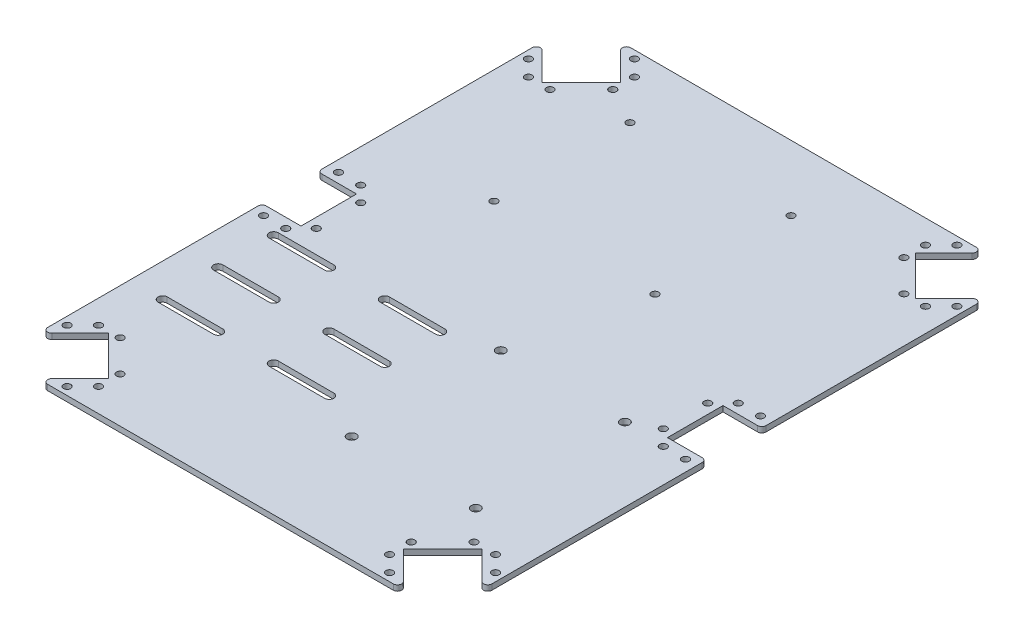
SolidWorks part; units mm, degrees
ref_plane "Front Plane" through (0, 0, 0) normal (0, 0, 1) x (1, 0, 0)
ref_plane "Top Plane" through (0, 0, 0) normal (0, 1, 0) x (1, 0, 0)
ref_plane "Right Plane" through (0, 0, 0) normal (1, 0, 0) x (0, 0, -1)
sketch "Sketch2" plane through (0, 0, 0) normal (0, 1, 0) x (1, 0, 0)
  line L0 (-80, 0) -> (80, 0) construction
  line L1 (-80, 105) -> (80, 105)
  line L2 (-80, 105) -> (-80, -105)
  line L3 (-80, -105) -> (80, -105)
  line L4 (80, 105) -> (80, -105)
  line L5 (80, 105) -> (0, 25) construction
  line L7 (0, 105) -> (0, -105) construction
  line L8 (52.4228, 88.7365) -> (48.5337, 92.6256) construction
  line L9 (48.5337, 92.6256) -> (52.4228, 96.5147) construction
  line L10 (52.4228, 96.5147) -> (58.0797, 102.1716) construction
  line L11 (58.0797, 102.1716) -> (60.9081, 105) construction
  circle A5 centre (52.4228, 88.7365) radius 1.3
  circle A6 centre (52.4228, 96.5147) radius 1.3
  circle A7 centre (58.0797, 102.1716) radius 1.3
  circle A8 centre (76, 13.5) radius 1.3
  circle A9 centre (68, 13.5) radius 1.3
  circle A10 centre (62.5, 8) radius 1.3
  circle A11 centre (62.5, -8) radius 1.3
  circle A12 centre (68, -13.5) radius 1.3
  circle A13 centre (76, -13.5) radius 1.3
  circle A14 centre (77.1716, 83.0797) radius 1.3
  circle A15 centre (71.5147, 77.4228) radius 1.3
  circle A16 centre (63.7365, 77.4228) radius 1.3
  circle A17 centre (77.1716, -83.0797) radius 1.3
  circle A18 centre (71.5147, -77.4228) radius 1.3
  circle A19 centre (63.7365, -77.4228) radius 1.3
  circle A20 centre (58.0797, -102.1716) radius 1.3
  circle A21 centre (52.4228, -96.5147) radius 1.3
  circle A22 centre (52.4228, -88.7365) radius 1.3
  circle A23 centre (-58.0797, 102.1716) radius 1.3
  circle A24 centre (-52.4228, 96.5147) radius 1.3
  circle A25 centre (-52.4228, 88.7365) radius 1.3
  circle A26 centre (-77.1716, 83.0797) radius 1.3
  circle A27 centre (-71.5147, 77.4228) radius 1.3
  circle A28 centre (-63.7365, 77.4228) radius 1.3
  circle A29 centre (-77.1716, -83.0797) radius 1.3
  circle A30 centre (-71.5147, -77.4228) radius 1.3
  circle A31 centre (-63.7365, -77.4228) radius 1.3
  circle A32 centre (-52.4228, -88.7365) radius 1.3
  circle A33 centre (-52.4228, -96.5147) radius 1.3
  circle A34 centre (-58.0797, -102.1716) radius 1.3
  circle A35 centre (-62.5, -8) radius 1.3
  circle A36 centre (-68, -13.5) radius 1.3
  circle A37 centre (-76, -13.5) radius 1.3
  circle A38 centre (-76, 13.5) radius 1.3
  circle A39 centre (-68, 13.5) radius 1.3
  circle A40 centre (-62.5, 8) radius 1.3
  point P0 (0, 0)
  point P27 (0, 0)
  dimension "D6" = 5.5
  dimension "D10" = 8
  dimension "D11" = 5.5
  dimension "D2" = 2.6
  dimension "D3" = 8
  dimension "D4" = 4
  dimension "D5" = 5.5
  dimension "D7" = 45
  dimension "D8" = 160
  dimension "D9" = 210
  dimension "D12" = 5.5
  dimension "D13" = 8
  dimension "D14" = 4
  dimension "D15" = 8
extrude "Boss-Extrude1" add sketch "Sketch2" along normal blind 2
sketch "Sketch3" plane through (0, 2, 0) normal (0, 1, 0) x (1, 0, 0)
  line L0 (0, -105) -> (0, 105) construction
  line L1 (-80, -105) -> (80, -105) construction
  line L2 (80, 105) -> (-80, 105) construction
  line L3 (-80, 0) -> (80, 0) construction
  line L4 (-80, 105) -> (-80, -105) construction
  line L5 (80, -105) -> (80, 105) construction
  line L6 (80, 105) -> (0, 25) construction
  line L7 (80, -10) -> (66, -10)
  line L8 (80, -10) -> (80, 10)
  line L9 (80, 10) -> (66, 10)
  line L10 (66, -10) -> (66, 10)
  line L11 (65.8579, 105) -> (53.1299, 92.2721)
  line L12 (53.1299, 92.2721) -> (67.2721, 78.1299)
  line L13 (67.2721, 78.1299) -> (80, 90.8579)
  line L14 (80, 90.8579) -> (80, 105)
  line L15 (80, 105) -> (65.8579, 105)
  line L16 (80, -90.8579) -> (80, -105)
  line L17 (67.2721, -78.1299) -> (80, -90.8579)
  line L18 (53.1299, -92.2721) -> (67.2721, -78.1299)
  line L19 (65.8579, -105) -> (53.1299, -92.2721)
  line L20 (80, -105) -> (65.8579, -105)
  line L21 (-80, 90.8579) -> (-80, 105)
  line L22 (-67.2721, 78.1299) -> (-80, 90.8579)
  line L23 (-53.1299, 92.2721) -> (-67.2721, 78.1299)
  line L24 (-65.8579, 105) -> (-53.1299, 92.2721)
  line L25 (-80, 105) -> (-65.8579, 105)
  line L26 (-80, 10) -> (-66, 10)
  line L27 (-66, -10) -> (-66, 10)
  line L28 (-80, -10) -> (-66, -10)
  line L29 (-80, -10) -> (-80, 10)
  line L30 (-67.2721, -78.1299) -> (-80, -90.8579)
  line L31 (-53.1299, -92.2721) -> (-67.2721, -78.1299)
  line L32 (-65.8579, -105) -> (-53.1299, -92.2721)
  line L33 (-80, -105) -> (-65.8579, -105)
  line L34 (-80, -90.8579) -> (-80, -105)
  dimension "D1" = 10
  dimension "D2" = 20
  dimension "D3" = 14
  dimension "D4" = 45
  dimension "D5" = 18
  dimension "D6" = 20
  dimension "D7" = 10
extrude "Cut-Extrude1" cut sketch "Sketch3" against normal up to surface (2 mm away) up to face at (0, 0, 0)
fillet "Fillet1" radius 1.5 12 edges at (-80, 1, 10) (-80, 1, -10) (-80, 1, 90.8579) (-65.8579, 1, 105) (65.8579, 1, 105) (80, 1, 90.8579) (80, 1, 10) (80, 1, -10) (80, 1, -90.8579) (65.8579, 1, -105) (-80, 1, -90.8579) (-65.8579, 1, -105)
sketch "Sketch4" plane through (0, 2, 0) normal (0, 1, 0) x (1, 0, 0)
  line L0 (80, 11.5) -> (80, 87.2365) construction
  line L1 (-39, 81.5) -> (19, 81.5) construction
  line L2 (-39, 81.5) -> (-39, 32.5) construction
  line L3 (-39, 32.5) -> (19, 32.5) construction
  line L4 (19, 81.5) -> (19, 32.5) construction
  line L5 (-42.5, 85) -> (42.5, 85) construction
  line L6 (-42.5, 85) -> (-42.5, 29) construction
  line L7 (-42.5, 29) -> (42.5, 29) construction
  line L8 (42.5, 85) -> (42.5, 29) construction
  line L9 (62.2365, 105) -> (-62.2365, 105) construction
  line L10 (-80, 87.2365) -> (-80, 11.5) construction
  circle A0 centre (-39, 81.5) radius 1.3
  circle A1 centre (19, 81.5) radius 1.3
  circle A2 centre (19, 32.5) radius 1.3
  circle A3 centre (-39, 32.5) radius 1.3
  dimension "D1" = 2.6
  dimension "D2" = 58
  dimension "D3" = 85
  dimension "D4" = 56
  dimension "D5" = 49
  dimension "D6" = 3.5
  dimension "D7" = 3.5
  dimension "D8" = 3.5
  dimension "D9" = 20
  dimension "D10" = 37.5
  dimension "D11" = 37.5
extrude "Cut-Extrude2" cut sketch "Sketch4" against normal up to surface (2 mm away) up to face at (0, 0, 0)
sketch "Sketch5" plane through (0, 2, 0) normal (0, 1, 0) x (1, 0, 0)
  line L4 (-68, -56.1887) -> (-48, -56.1887)
  line L12 (-67.9995, -59.4887) -> (-47.8563, -59.4824)
  line L13 (-68, -36.1887) -> (-48, -36.1887)
  line L14 (-67.9995, -39.4887) -> (-47.8563, -39.4824)
  line L15 (-68, -16.1887) -> (-48, -16.1887)
  line L16 (-67.9995, -19.4887) -> (-47.8563, -19.4824)
  line L17 (-80, -11.5) -> (-80, -87.2365) construction
  line L18 (-38, -105) -> (-38, 105) construction
  line L19 (-62.2365, -105) -> (62.2365, -105) construction
  line L20 (62.2365, 105) -> (-62.2365, 105) construction
  line L22 (-8.0005, -19.4887) -> (-28.1437, -19.4824)
  line L23 (-8, -16.1887) -> (-28, -16.1887)
  line L24 (-8.0005, -39.4887) -> (-28.1437, -39.4824)
  line L25 (-8, -36.1887) -> (-28, -36.1887)
  line L26 (-8.0005, -59.4887) -> (-28.1437, -59.4824)
  line L27 (-8, -56.1887) -> (-28, -56.1887)
  arc A0 (-68, -56.1887) -> (-67.9995, -59.4887) centre (-68, -57.8387) ccw
  arc A1 (-47.8563, -59.4824) -> (-48, -56.1887) centre (-48, -57.8387) ccw
  arc A12 (-68, -36.1887) -> (-67.9995, -39.4887) centre (-68, -37.8387) ccw
  arc A13 (-47.8563, -39.4824) -> (-48, -36.1887) centre (-48, -37.8387) ccw
  arc A14 (-68, -16.1887) -> (-67.9995, -19.4887) centre (-68, -17.8387) ccw
  arc A15 (-47.8563, -19.4824) -> (-48, -16.1887) centre (-48, -17.8387) ccw
  arc A16 (-28.1437, -19.4824) -> (-28, -16.1887) centre (-28, -17.8387) cw
  arc A17 (-8, -16.1887) -> (-8.0005, -19.4887) centre (-8, -17.8387) cw
  arc A18 (-28.1437, -39.4824) -> (-28, -36.1887) centre (-28, -37.8387) cw
  arc A19 (-8, -36.1887) -> (-8.0005, -39.4887) centre (-8, -37.8387) cw
  arc A20 (-28.1437, -59.4824) -> (-28, -56.1887) centre (-28, -57.8387) cw
  arc A21 (-8, -56.1887) -> (-8.0005, -59.4887) centre (-8, -57.8387) cw
  point P44 (0, 0)
  dimension "D1" = 3.3
  dimension "D2" = 20
  dimension "D4" = 12
  dimension "D5" = 10
  dimension "D3" = 3
extrude "Cut-Extrude3" cut sketch "Sketch5" against normal up to surface (2 mm away)
sketch "Sketch6" plane through (0, 2, 0) normal (0, 1, 0) x (1, 0, 0)
  line L1 (7.1401, -68.1784) -> (7.1401, -11.1784) construction
  line L2 (7.1401, -68.1784) -> (55.1401, -68.1784) construction
  line L3 (55.1401, -68.1784) -> (55.1401, -11.1784) construction
  line L4 (7.1401, -11.1784) -> (55.1401, -11.1784) construction
  line L5 (8.7901, -66.5284) -> (8.7901, -12.8284) construction
  line L6 (8.7901, -66.5284) -> (53.4901, -66.5284) construction
  line L7 (53.4901, -66.5284) -> (53.4901, -12.8284) construction
  line L8 (8.7901, -12.8284) -> (53.4901, -12.8284) construction
  circle A0 centre (8.7901, -66.5284) radius 1.65
  circle A1 centre (8.7901, -12.8284) radius 1.65
  circle A2 centre (53.4901, -12.8284) radius 1.65
  circle A3 centre (53.4901, -66.5284) radius 1.65
  dimension "D3" = 3.3
  dimension "D1" = 48
  dimension "D2" = 57
  dimension "D4" = 1.65
  dimension "D5" = 1.65
  dimension "D6" = 1.65
  dimension "D7" = 1.65
extrude "Cut-Extrude4" cut sketch "Sketch6" against normal up to surface (2 mm away) up to face at (-18.0176, 0, 37.82)
